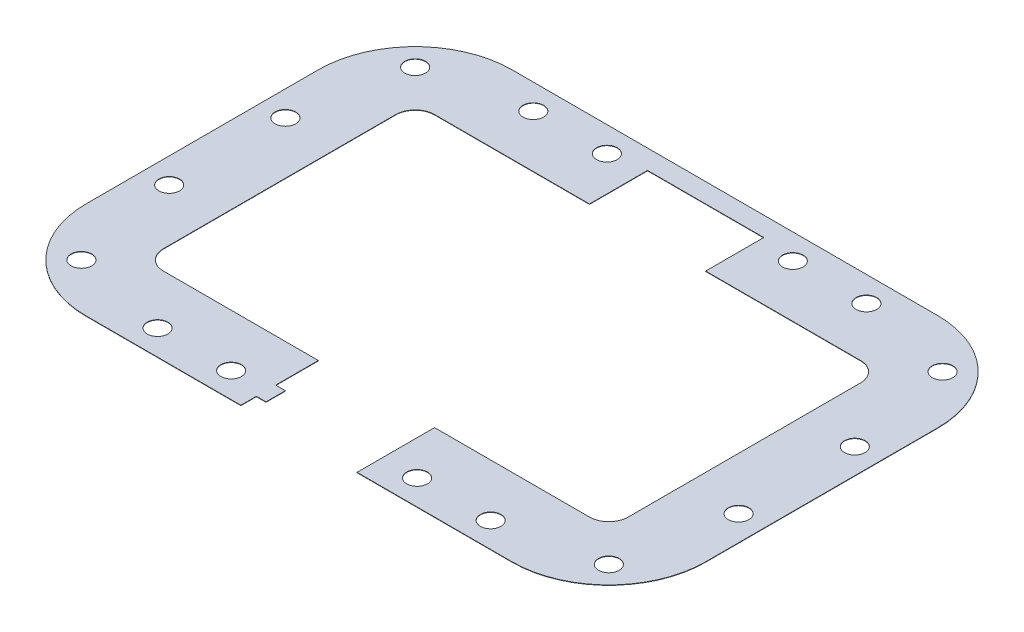
SolidWorks part; units mm, degrees
ref_plane "Front Plane" through (0, 0, 0) normal (0, 0, 1) x (1, 0, 0)
ref_plane "Top Plane" through (0, 0, 0) normal (0, 1, 0) x (1, 0, 0)
ref_plane "Right Plane" through (0, 0, 0) normal (1, 0, 0) x (0, 0, -1)
sketch "Sketch1" plane through (0, 0, 0) normal (0, 1, 0) x (1, 0, 0)
  line L1 (101.6, -69.85) -> (-101.6, -69.85)
  line L2 (101.6, -69.85) -> (101.6, 69.85)
  line L3 (101.6, 69.85) -> (-101.6, 69.85)
  line L4 (-101.6, -69.85) -> (-101.6, 69.85)
  line L5 (101.6, -69.85) -> (-101.6, 69.85) construction
  line L6 (101.6, 69.85) -> (-101.6, -69.85) construction
  point P0 (0, 0)
  dimension "D1" = 203.2
  dimension "D2" = 139.7
extrude "Base Extrude" add sketch "Sketch1" along normal blind 0.127
sketch "Sketch2" plane through (0, 0.127, 0) normal (0, 1, 0) x (1, 0, 0)
  line L1 (76.2, -44.45) -> (-76.2, -44.45)
  line L2 (76.2, -44.45) -> (76.2, 44.45)
  line L3 (76.2, 44.45) -> (-76.2, 44.45)
  line L4 (-76.2, -44.45) -> (-76.2, 44.45)
  line L5 (76.2, -44.45) -> (-76.2, 44.45) construction
  line L6 (76.2, 44.45) -> (-76.2, -44.45) construction
  point P0 (0, 0)
  dimension "D1" = 152.4
  dimension "D2" = 88.9
extrude "Center Cut" cut sketch "Sketch2" against normal through all
sketch "Sketch3" plane through (0, 0.127, 0) normal (0, 1, 0) x (1, 0, 0)
  line L0 (0, 0) -> (0, -69.85) construction
  line L1 (-101.6, -69.85) -> (101.6, -69.85) construction
  line L2 (-76.2, -44.45) -> (76.2, -44.45) construction
  line L3 (19.05, -152.4) -> (-19.05, -152.4)
  line L4 (19.05, -152.4) -> (19.05, 63.5)
  line L5 (19.05, 63.5) -> (-19.05, 63.5)
  line L6 (-19.05, -152.4) -> (-19.05, 63.5)
  line L7 (19.05, -152.4) -> (-19.05, 63.5) construction
  line L8 (19.05, 63.5) -> (-19.05, -152.4) construction
  line L9 (101.6, 69.85) -> (-101.6, 69.85) construction
  point P5 (0, -44.45)
  dimension "D1" = 6.35
  dimension "D2" = 38.1
extrude "Vetical Cut" cut sketch "Sketch3" against normal through all
fillet "Fillet 1" radius 31.75 4 edges at (-101.6, 0.0635, -69.85) (101.6, 0.0635, -69.85) (101.6, 0.0635, 69.85) (-101.6, 0.0635, 69.85)
sketch "Sketch4" plane through (0, 0.127, 0) normal (0, 1, 0) x (1, 0, 0)
  line L6 (-22.225, -64.77) -> (-15.875, -64.77)
  line L7 (-22.225, -64.77) -> (-22.225, -58.42)
  line L8 (-22.225, -58.42) -> (-15.875, -58.42)
  line L9 (-15.875, -64.77) -> (-15.875, -58.42)
  line L10 (19.05, -61.595) -> (69.85, -61.595)
  line L11 (93.345, -38.1) -> (93.345, 38.1)
  line L12 (69.85, 61.595) -> (-69.85, 61.595)
  line L13 (-93.345, 38.1) -> (-93.345, -38.1)
  line L14 (-69.85, -61.595) -> (-19.05, -61.595)
  line L15 (19.05, -61.595) -> (69.85, -61.595) construction
  line L16 (93.345, -38.1) -> (93.345, 38.1) construction
  line L17 (69.85, 61.595) -> (-69.85, 61.595) construction
  line L26 (-93.345, 38.1) -> (-93.345, -38.1) construction
  line L27 (-69.85, -61.595) -> (-19.05, -61.595) construction
  line L28 (-22.225, -64.77) -> (-15.875, -58.42) construction
  line L29 (-22.225, -58.42) -> (-15.875, -64.77) construction
  arc A14 (69.85, -61.595) -> (93.345, -38.1) centre (69.85, -38.1) ccw
  arc A15 (93.345, 38.1) -> (69.85, 61.595) centre (69.85, 38.1) ccw
  arc A16 (-69.85, 61.595) -> (-93.345, 38.1) centre (-69.85, 38.1) ccw
  arc A17 (-93.345, -38.1) -> (-69.85, -61.595) centre (-69.85, -38.1) ccw
  arc A18 (69.85, -61.595) -> (93.345, -38.1) centre (69.85, -38.1) ccw construction
  arc A19 (93.345, 38.1) -> (69.85, 61.595) centre (69.85, 38.1) ccw construction
  arc A20 (-69.85, 61.595) -> (-93.345, 38.1) centre (-69.85, 38.1) ccw construction
  arc A21 (-93.345, -38.1) -> (-69.85, -61.595) centre (-69.85, -38.1) ccw construction
  dimension "D2" = 6.35
  dimension "D3" = 6.35
  dimension "D1" = 8.255
extrude "Square Extrude" add sketch "Sketch4" against normal blind 0.127
sketch "Sketch7" plane through (0, 0.127, 0) normal (0, 1, 0) x (1, 0, 0)
  line L5 (-101.6, 0) -> (101.6, 0) construction
  line L6 (-101.6, 38.1) -> (-101.6, -38.1) construction
  line L7 (101.6, -38.1) -> (101.6, 38.1) construction
  line L9 (0, 69.85) -> (0, -73.5176) construction
  line L10 (19.05, -61.595) -> (69.85, -61.595)
  line L11 (93.345, -38.1) -> (93.345, 38.1)
  line L12 (-69.85, -61.595) -> (-19.05, -61.595)
  line L13 (-93.345, 38.1) -> (-93.345, -38.1)
  line L14 (69.85, 61.595) -> (-69.85, 61.595)
  line L15 (19.05, -61.595) -> (69.85, -61.595) construction
  line L16 (93.345, -38.1) -> (93.345, 38.1) construction
  line L17 (-69.85, -61.595) -> (-19.05, -61.595) construction
  line L18 (-93.345, 38.1) -> (-93.345, -38.1) construction
  line L19 (69.85, 61.595) -> (-69.85, 61.595) construction
  line L20 (69.85, 69.85) -> (-69.85, 69.85) construction
  circle A5 centre (-93.345, -19.05) radius 3.3782
  circle A6 centre (-86.4635, -54.7135) radius 3.3782
  circle A7 centre (-30.48, -61.595) radius 3.3782
  circle A8 centre (-54.61, -61.595) radius 3.3782
  arc A9 (69.85, -61.595) -> (93.345, -38.1) centre (69.85, -38.1) ccw
  arc A10 (93.345, 38.1) -> (69.85, 61.595) centre (69.85, 38.1) ccw
  arc A11 (-93.345, -38.1) -> (-69.85, -61.595) centre (-69.85, -38.1) ccw
  arc A12 (-69.85, 61.595) -> (-93.345, 38.1) centre (-69.85, 38.1) ccw
  arc A13 (69.85, -61.595) -> (93.345, -38.1) centre (69.85, -38.1) ccw construction
  arc A14 (93.345, 38.1) -> (69.85, 61.595) centre (69.85, 38.1) ccw construction
  arc A15 (-93.345, -38.1) -> (-69.85, -61.595) centre (-69.85, -38.1) ccw construction
  arc A16 (-69.85, 61.595) -> (-93.345, 38.1) centre (-69.85, 38.1) ccw construction
  point P6 (-93.345, 0)
  dimension "D2" = 19.05
  dimension "D3" = 30.48
  dimension "D4" = 54.61
  dimension "D1" = 8.255
extrude "Circular Extrude" cut sketch "Sketch7" against normal through all
mirror "Mirror 1" about plane through (0, 0, 0) normal (1, 0, 0) of "Circular Extrude"
mirror "Mirror 2" about plane through (0, 0, 0) normal (0, 0, 1) of "Mirror 1", "Circular Extrude"
fillet "Fillet 2" radius 6.35 4 edges at (76.2, 0.0635, 44.45) (76.2, 0.0635, -44.45) (-76.2, 0.0635, -44.45) (-76.2, 0.0635, 44.45)
